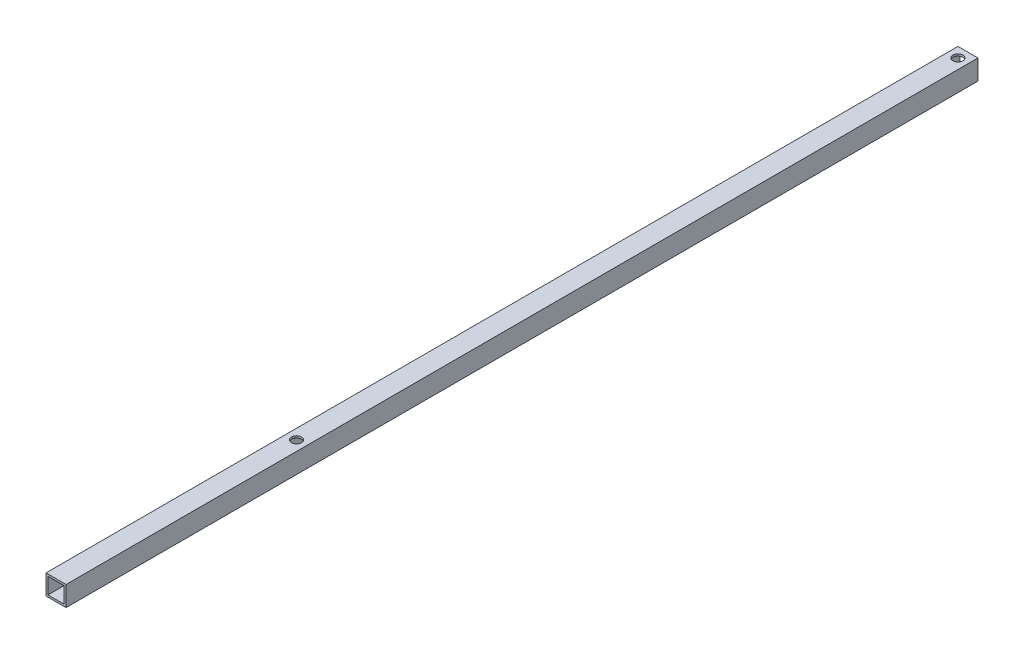
SolidWorks part; units mm, degrees
ref_plane "Front Plane" through (0, 0, 0) normal (0, 0, 1) x (1, 0, 0)
ref_plane "Top Plane" through (0, 0, 0) normal (0, 1, 0) x (1, 0, 0)
ref_plane "Right Plane" through (0, 0, 0) normal (1, 0, 0) x (0, 0, -1)
sketch "Sketch1" plane through (0, 0, 0) normal (0, 0, 1) x (1, 0, 0)
  line L0 (2.54, 22.86) -> (22.86, 22.86)
  line L1 (0, 0) -> (25.4, 0)
  line L2 (0, 0) -> (0, 25.4)
  line L3 (0, 25.4) -> (25.4, 25.4)
  line L4 (25.4, 0) -> (25.4, 25.4)
  line L5 (22.86, 2.54) -> (22.86, 22.86)
  line L6 (2.54, 2.54) -> (22.86, 2.54)
  line L7 (2.54, 2.54) -> (2.54, 22.86)
  dimension "D1" = 25.4
  dimension "D2" = 25.4
  dimension "D3" = 2.54
extrude "Boss-Extrude1" add sketch "Sketch1" along normal blind 1155.7
sketch "Sketch2" plane through (0, 0, 0) normal (0, -1, 0) x (1, 0, 0)
  line L1 (0, 0) -> (25.4, 0) construction
  circle A0 centre (12.7, 12.7) radius 6.35
  point P2 (0, 0)
  point P3 (12.7, 0)
  point P6 (0, 0)
  point P7 (0, 0)
  dimension "D1" = 12.7
  dimension "D2" = 12.7
extrude "Cut-Extrude1" cut sketch "Sketch2" against normal through all
sketch "Sketch3" plane through (0, 0, 0) normal (0, -1, 0) x (1, 0, 0)
  line L0 (0, 1155.7) -> (25.4, 1155.7) construction
  circle A0 centre (12.7, 850.9) radius 6.35
  point P2 (0, 0)
  point P5 (12.7, 1155.7)
  point P6 (0, 0)
  dimension "D1" = 12.7
  dimension "D2" = 304.8
extrude "Cut-Extrude2" cut sketch "Sketch3" against normal through all both and the other way through all
